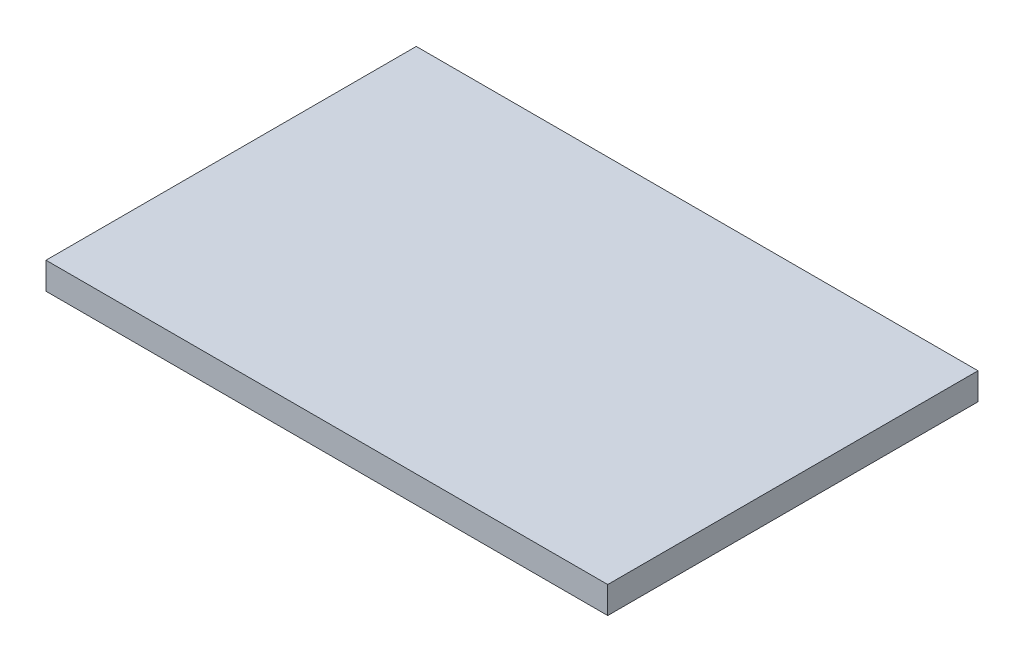
SolidWorks part; units mm, degrees
ref_plane "Front Plane" through (0, 0, 0) normal (0, 0, 1) x (1, 0, 0)
ref_plane "Top Plane" through (0, 0, 0) normal (0, 1, 0) x (1, 0, 0)
ref_plane "Right Plane" through (0, 0, 0) normal (1, 0, 0) x (0, 0, -1)
sketch "Sketch1" plane through (0, 0, 0) normal (0, 1, 0) x (1, 0, 0)
  line L1 (0, 0) -> (355, 0)
  line L2 (0, 0) -> (0, -234)
  line L3 (0, -234) -> (355, -234)
  line L4 (355, 0) -> (355, -234)
  dimension "D1" = 355
  dimension "D2" = 234
extrude "Boss-Extrude1" add sketch "Sketch1" along normal blind 17
